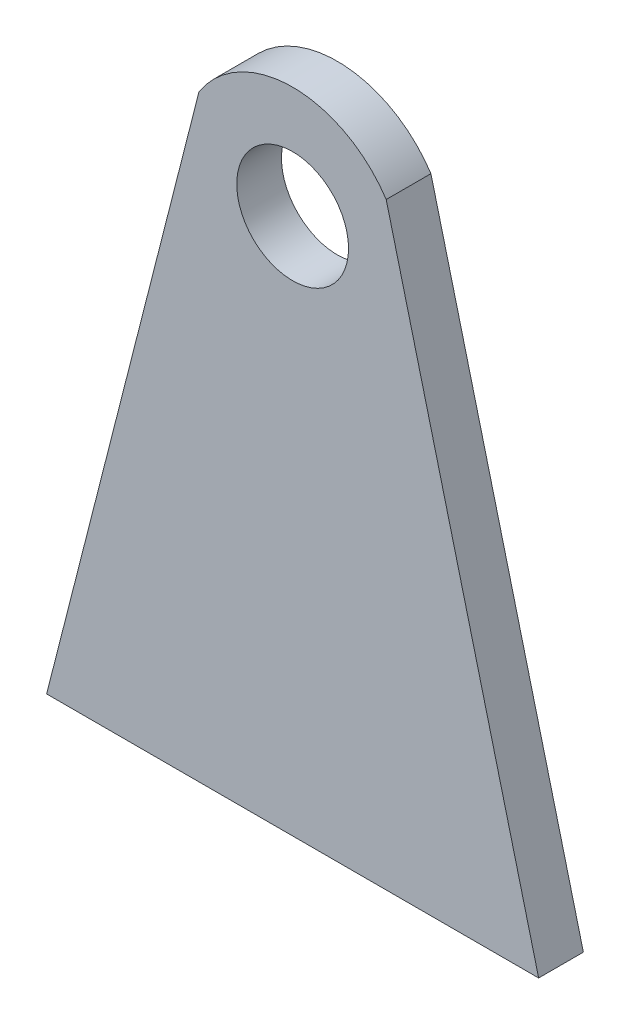
SolidWorks part; units mm, degrees
ref_plane "Front Plane" through (0, 0, 0) normal (0, 0, 1) x (1, 0, 0)
ref_plane "Top Plane" through (0, 0, 0) normal (0, 1, 0) x (1, 0, 0)
ref_plane "Right Plane" through (0, 0, 0) normal (1, 0, 0) x (0, 0, -1)
sketch "Sketch2" plane through (0, 0, 0) normal (0, 0, 1) x (1, 0, 0)
  line L0 (0, 95) -> (0, -145) construction
  line L1 (110, -145) -> (-110, -145)
  line L5 (110, -145) -> (-110, 145) construction
  line L6 (110, 145) -> (-110, -145) construction
  line L7 (0, -145) -> (-192.8667, 30.4333) construction
  line L8 (-192.8667, 30.4333) -> (-372.5333, 84.7) construction
  line L9 (110, -145) -> (41.8381, 122.3784)
  line L10 (-110, -145) -> (-41.8381, 122.3784)
  arc A0 (41.8381, 122.3784) -> (-41.8381, 122.3784) centre (0, 95) ccw
  point P0 (0, 0)
  dimension "D4" = 100
  dimension "D1" = 220
  dimension "D2" = 290
  dimension "D3" = 240
extrude "Boss-Extrude1" add sketch "Sketch2" along normal blind 20
sketch "Sketch3" plane through (0, 0, 20) normal (0, 0, 1) x (1, 0, 0)
  line L0 (-110, -145) -> (110, -145) construction
  circle A0 centre (0, 95) radius 25
  dimension "D2" = 50
  dimension "D1" = 240
extrude "Cut-Extrude1" cut sketch "Sketch3" against normal blind 20
